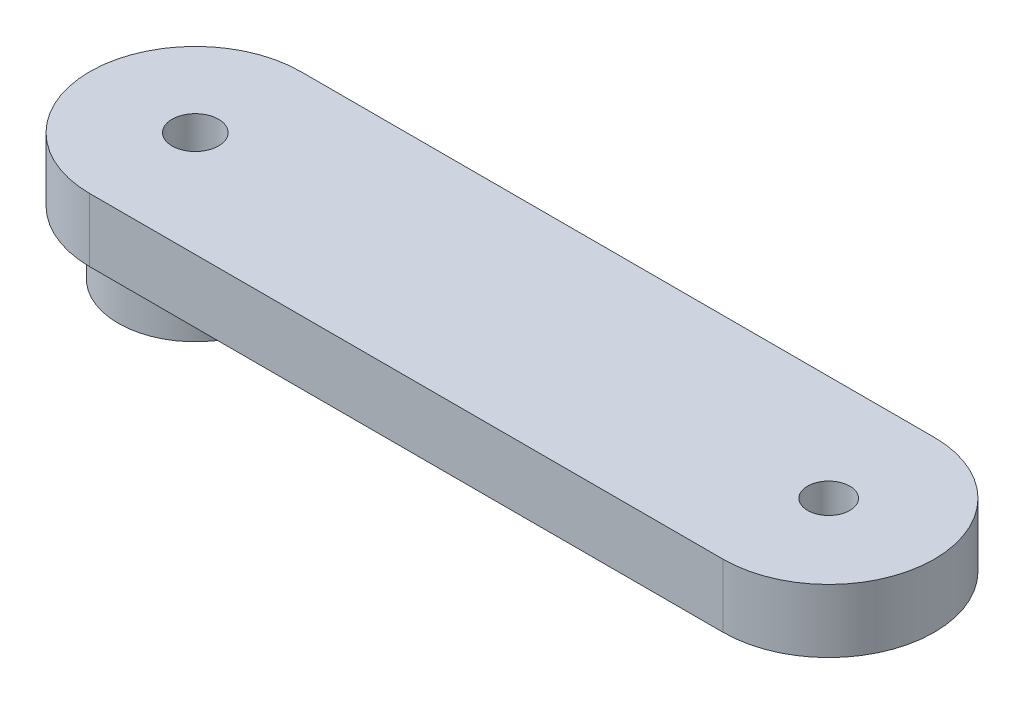
SolidWorks part; units mm, degrees
ref_plane "Front Plane" through (0, 0, 0) normal (0, 0, 1) x (1, 0, 0)
ref_plane "Top Plane" through (0, 0, 0) normal (0, 1, 0) x (1, 0, 0)
ref_plane "Right Plane" through (0, 0, 0) normal (1, 0, 0) x (0, 0, -1)
sketch "Sketch1" plane through (0, 0, 0) normal (0, 1, 0) x (1, 0, 0)
  line L0 (0, 0) -> (30, 0) construction
  line L1 (0, 5) -> (30, 5)
  line L2 (0, -5) -> (30, -5)
  arc A0 (0, 5) -> (0, -5) centre (0, 0) ccw
  arc A1 (30, -5) -> (30, 5) centre (30, 0) ccw
  point P3 (15, 0)
  dimension "D1" = 5
  dimension "D2" = 30
extrude "Boss-Extrude1" add sketch "Sketch1" along normal blind 3 contours A0 L2 A1 L1
sketch "Sketch2" plane through (0, 0, 0) normal (0, -1, 0) x (1, 0, 0)
  circle A0 centre (0, 0) radius 3.65
  dimension "D1" = 7.3
extrude "Boss-Extrude2" add sketch "Sketch2" along normal blind 3
sketch "Sketch3" plane through (0, -3, 0) normal (0, -1, 0) x (1, 0, 0)
  circle A0 centre (0, 0) radius 1.1
  dimension "D1" = 2.2
extrude "Cut-Extrude1" cut sketch "Sketch3" against normal up to surface (6 mm away) up to face at (15, 3, 0)
sketch "Sketch5" plane through (0, -3, 0) normal (0, -1, 0) x (1, 0, 0)
  circle A0 centre (0, 0) radius 2.65
  circle A1 centre (0, 0) radius 3.65 construction
  dimension "D1" = 1
extrude "Cut-Extrude2" cut sketch "Sketch5" against normal blind 4
sketch "Sketch6" plane through (0, 3, 0) normal (0, 1, 0) x (1, 0, 0)
  circle A0 centre (0, 0) radius 2.6
  dimension "D1" = 5.2
ref_point "Point1"
sketch "Sketch7" plane through (0, 3, 0) normal (0, 1, 0) x (1, 0, 0)
  circle A0 centre (30, 0) radius 1
  dimension "D1" = 2
extrude "Cut-Extrude4" cut sketch "Sketch7" against normal up to surface (3 mm away) up to face at (0, 0, 3.65)
